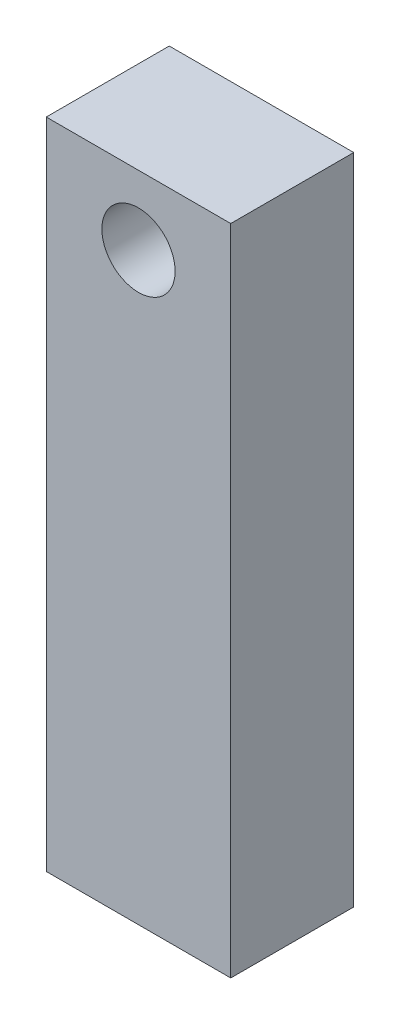
SolidWorks part; units mm, degrees
material "Gray Cast Iron"
ref_plane "Front Plane" through (0, 0, 0) normal (0, 0, 1) x (1, 0, 0)
ref_plane "Top Plane" through (0, 0, 0) normal (0, 1, 0) x (1, 0, 0)
ref_plane "Right Plane" through (0, 0, 0) normal (1, 0, 0) x (0, 0, -1)
sketch "Sketch1" plane through (0, 0, 0) normal (0, 1, 0) x (1, 0, 0)
  line L0 (-12, -8) -> (12, -8)
  line L1 (12, -8) -> (12, 8)
  line L2 (12, 8) -> (-12, 8)
  line L3 (-12, 8) -> (-12, -8)
  dimension "D1" = 24
  dimension "D2" = 16
  dimension "D3" = 12
  dimension "D4" = 8
extrude "Boss-Extrude1" add sketch "Sketch1" along normal blind 85
sketch "Sketch2" plane through (0, 0, 0) normal (0, 0, 1) x (1, 0, 0)
  circle A0 centre (0, 76) radius 4.7625
  dimension "D2" = 9.525
  dimension "D1" = 76
extrude "Cut-Extrude1" cut sketch "Sketch2" against normal mid plane 20
